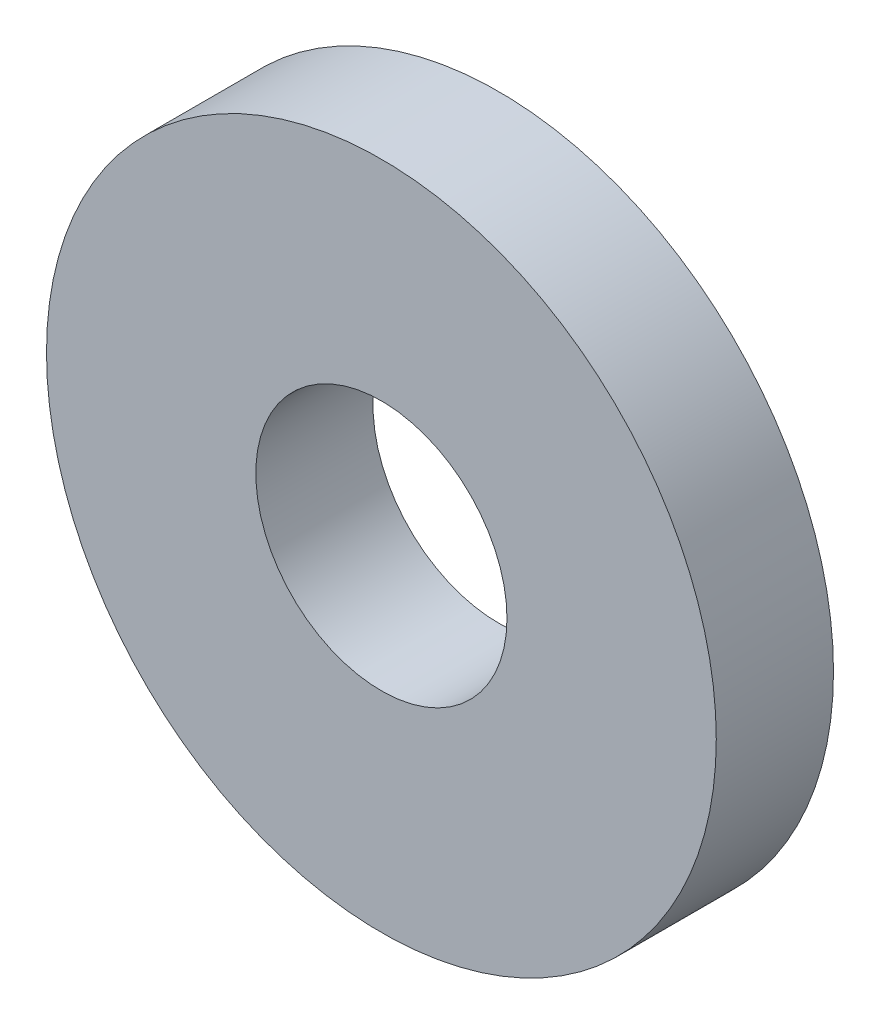
SolidWorks part; units mm, degrees
material "Alumina"
ref_plane "Front Plane" through (0, 0, 0) normal (0, 0, 1) x (1, 0, 0)
ref_plane "Top Plane" through (0, 0, 0) normal (0, 1, 0) x (1, 0, 0)
ref_plane "Right Plane" through (0, 0, 0) normal (1, 0, 0) x (0, 0, -1)
sketch "Sketch1" plane through (0, 0, 0) normal (0, 0, 1) x (1, 0, 0)
  circle A0 centre (0, 0) radius 20
  circle A1 centre (0, 0) radius 7.5
  dimension "D1" = 40
  dimension "D2" = 15
extrude "Boss-Extrude1" add sketch "Sketch1" along normal blind 7
